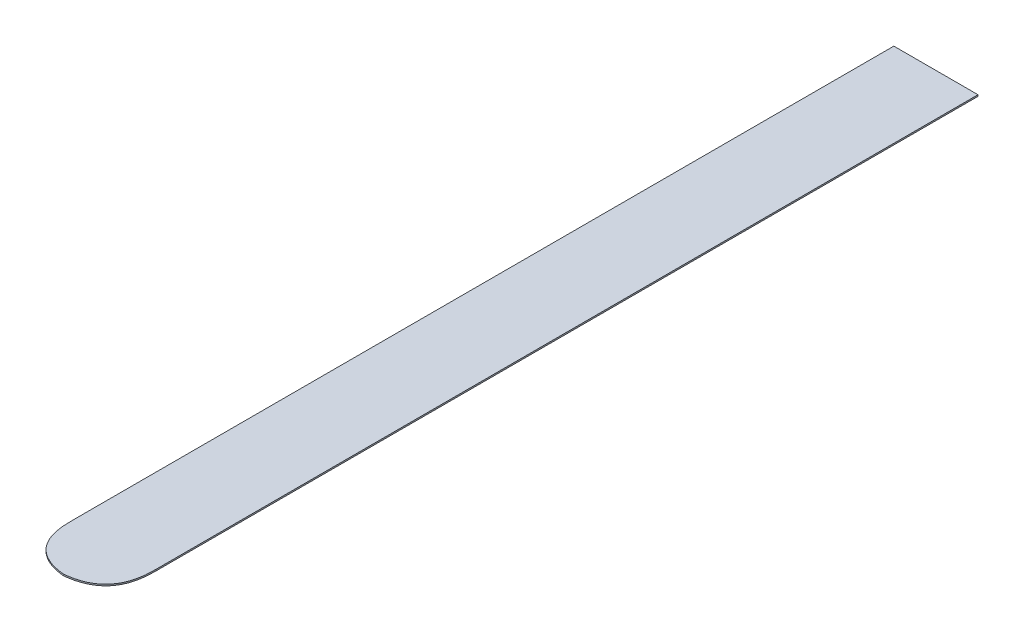
SolidWorks part; units mm, degrees
ref_plane "Front Plane" through (0, 0, 0) normal (0, 0, 1) x (1, 0, 0)
ref_plane "Top Plane" through (0, 0, 0) normal (0, 1, 0) x (1, 0, 0)
ref_plane "Right Plane" through (0, 0, 0) normal (1, 0, 0) x (0, 0, -1)
sketch "Sketch2" plane through (0, 0, 0) normal (0, 1, 0) x (1, 0, 0)
  line L0 (0, -6122.228) -> (0, 2040.7427)
  line L1 (0, 0) -> (-18096.1342, 0) construction
  line L2 (0, 0) -> (-21640.8, -16307.5125) construction
  line L3 (-21640.8, -18450.2946) -> (-21640.8, -15593.2518)
  line L4 (-21640.8, -15593.2518) -> (0, 2040.7427)
  line L5 (-21640.8, -18450.2946) -> (0, -6122.228)
  line L6 (-9083.802, -5361.1886) -> (-9083.802, -6845.1358) construction
  line L7 (-9083.802, -6845.1358) -> (-9083.802, -11296.9774) construction
  line L8 (-9083.802, -6845.1358) -> (0, -6845.1358) construction
  line L9 (0, 408.1485) -> (-18440.4, -13713.752)
  line L10 (0, -35661.6) -> (-7316.724, -42249.6079) construction
  line L11 (0, -35661.6) -> (-8167.6786, -35661.6) construction
  line L12 (0, -34539.0879) -> (0, -39029.1363)
  line L13 (-7316.724, -43428.2455) -> (-7316.724, -41856.7287)
  line L14 (-7316.724, -41856.7287) -> (0, -34539.0879)
  line L15 (0, -39029.1363) -> (-7316.724, -43428.2455)
  line L16 (-2544.3607, -37083.7674) -> (-2544.3607, -37952.5526) construction
  line L17 (-2544.3607, -37952.5526) -> (-2544.3607, -40558.9084) construction
  line L18 (-2544.3607, -37952.5526) -> (0, -37952.5526) construction
  line L19 (-18440.4, -13713.752) -> (-18440.4, -15898.787)
  line L20 (-18440.4, -15898.787) -> (0, -4489.6339)
  line L21 (0, 408.1485) -> (0, -4489.6339) construction
  line L22 (0, -4489.6339) -> (0, 408.1485) construction
  line L23 (0, 408.1485) -> (0, -2040.7427) construction
  line L24 (0, 408.1485) -> (0, -4489.6339) construction
  line L25 (0, -2040.7427) -> (-18440.4, -14806.2695) construction
  line L26 (0, 408.1485) -> (-21640.8, -16164.6603) construction
  line L27 (-6975.7046, -4933.9377) -> (-6975.7046, -6869.7347) construction
  line L28 (-6975.7046, -6869.7347) -> (-6975.7046, -8805.5317) construction
  line L29 (-6975.7046, -6869.7347) -> (0, -6869.7347) construction
  dimension "Wing Sweep" = 37
  dimension "Half Span" = 21640.8
  dimension "Wing Root" = 8162.9707
  dimension "D4" = 2040.7427
  dimension "Wing Tip" = 2857.0428
  dimension "D6" = 714.2607
  dimension "Wing YBar" = 9083.802
  dimension "Tail Sweep" = 42
  dimension "Tail Root" = 4490.0484
  dimension "D10" = 1122.5121
  dimension "Tail Tip" = 1571.5168
  dimension "D12" = 392.8792
  dimension "D13" = 7316.724
  dimension "Tail Ybar" = 2544.3607
  dimension "First Spar" = 1632.5941
  dimension "Second Spar" = 6530.3766
  dimension "Fuel Tip" = 2185.035
  dimension "Tip Spar" = 571.4086
  dimension "Fuel Ybar" = 6975.7046
  dimension "Fuel Tank Length" = 18440.4
  dimension "Tail Arm" = 35661.6
sketch "Sketch4" plane through (0, 0, 0) normal (0, 1, 0) x (1, 0, 0)
  line L0 (0, 17538.8642) -> (0, -40677.9358) construction
  line L1 (-2194.56, 17538.8642) -> (2194.56, 17538.8642) construction
  line L2 (-2194.56, 10955.1842) -> (-2194.56, -31899.6958)
  line L3 (-2194.56, -40677.9358) -> (2194.56, -40677.9358) construction
  line L4 (2194.56, 10955.1842) -> (2194.56, -31899.6958)
  line L5 (0, -6122.228) -> (0, 2040.7427) construction
  line L6 (-9083.802, -6845.1358) -> (0, -6845.1358) construction
  line L7 (-2544.3607, -37952.5526) -> (0, -37952.5526) construction
  line L8 (0, 0) -> (-21640.8, -16307.5125) construction
  line L9 (-21640.8, -15593.2518) -> (0, 2040.7427) construction
  line L10 (-8474.964, 1555.5245) -> (-5807.964, 1555.5245)
  line L11 (-8474.964, 1555.5245) -> (-8474.964, -5453.2245)
  line L12 (-8474.964, -5453.2245) -> (-5807.964, -5453.2245)
  line L13 (-5807.964, 1555.5245) -> (-5807.964, -5453.2245)
  line L14 (2194.56, 10955.1842) -> (-2194.56, 10955.1842)
  arc A0 (-2194.56, -31899.6958) -> (2194.56, -31899.6958) centre (0, -31899.6958) ccw construction
  spline S0 degree 2 poles (-2194.56, 10955.1842) (-1797.8006, 14477.4245) (0, 17538.8642) knots 0 0 0 1 1 1 construction
  spline S1 degree 2 poles (2194.56, 10955.1842) (1797.8006, 14477.4245) (0, 17538.8642) knots 0 0 0 1 1 1 construction
  spline S2 degree 3 poles (-2194.56, -31899.6958) (-1988.0555, -33894.3006) (-2427.5411, -36708.4869) (-673.4811, -39045.278) (0, -39029.1363) knots 0 0 0 0 0.771523 1 1 1 1 construction
  spline S3 degree 3 poles (2194.56, -31899.6958) (1988.0555, -33894.3006) (2427.5411, -36708.4869) (673.4811, -39045.278) (0, -39029.1363) knots 0 0 0 0 0.771523 1 1 1 1 construction
  spline S4 degree 2 poles (-2194.56, -31899.6958) (-2243.3787, -34319.121) (0, -34539.0879) knots 0 0 0 1 1 1
  spline S5 degree 2 poles (2194.56, -31899.6958) (2243.3787, -34319.121) (0, -34539.0879) knots 0 0 0 1 1 1
  point P6 (0, 10955.1842)
  point P7 (0, -31899.6958)
  point P8 (0, -6845.1358)
  point P15 (0, -34094.2558)
  point P28 (-7141.464, 1555.5245)
  point P29 (-7141.464, -3778.4755)
  point P35 (-7141.464, -5381.4791)
  point P44 (-7141.464, -1247.9751)
  dimension "Fuse Length" = 58216.8
  dimension "Fuse Dia" = 4389.12
  dimension "D3" = 6583.68
  dimension "D4" = 8778.24
  dimension "D6" = 7141.464
  dimension "Engine Dia" = 2667
  dimension "Engine Length" = 7008.749
  dimension "D9" = 5334
  dimension "D10" = 2803.4996
  dimension "D11" = 5597.1607
  dimension "D2" = 24384
extrude "Boss-Extrude1" add sketch "Sketch4" along normal blind 76.2 contours L14 L2 S4 S5 L4
sketch "Sketch40" plane through (0, 0, 0) normal (0, 1, 0) x (1, 0, 0)
  line L0 (-2194.56, 17538.8642) -> (2194.56, 17538.8642) construction
  point P0 (0, -6623.5767)
  point P1 (0, -6643.3582)
  point P2 (0, -6753.4011)
  point P3 (0, -6454.3517)
  point P4 (0, 0)
  dimension "CG Design" = 24162.4409
  dimension "CG Empty" = 24182.2224
  dimension "CG Ferry" = 24292.2654
  dimension "CG Landing" = 23993.2159
equation "\"D6@Sketch2\" = \"Wing Tip@Sketch2\" / 4"
equation "\"D4@Sketch2\" = \"Wing Root@Sketch2\" / 4"
equation "\"D10@Sketch2\" = \"Tail Root@Sketch2\" / 4"
equation "\"D12@Sketch2\" = \"Tail Tip@Sketch2\" / 4"
equation "\"D13@Sketch2\"=48.01/2"
equation "\"First Spar@Sketch2\"=0.2 * \"Wing Root@Sketch2\""
equation "\"Second Spar@Sketch2\"    = 0.8 * \"Wing Root@Sketch2\""
equation "\"Tip Spar@Sketch2\"=0.2 * \"Wing Tip@Sketch2\""
equation "\"D3@Sketch4\" = 1.5 * \"Fuse Dia@Sketch4\""
equation "\"D4@Sketch4\" = 2 * \"Fuse Dia@Sketch4\""
equation "\"D6@Sketch4\" = 0.33 * \"Half Span@Sketch2\""
equation "\"D9@Sketch4\" = 2 * \"Engine Dia@Sketch4\""
equation "\"D10@Sketch4\" = 0.40 * \"Engine Length@Sketch4\""
equation "\"D4@Sketch11\"=.35*\"D3@Sketch11\""
